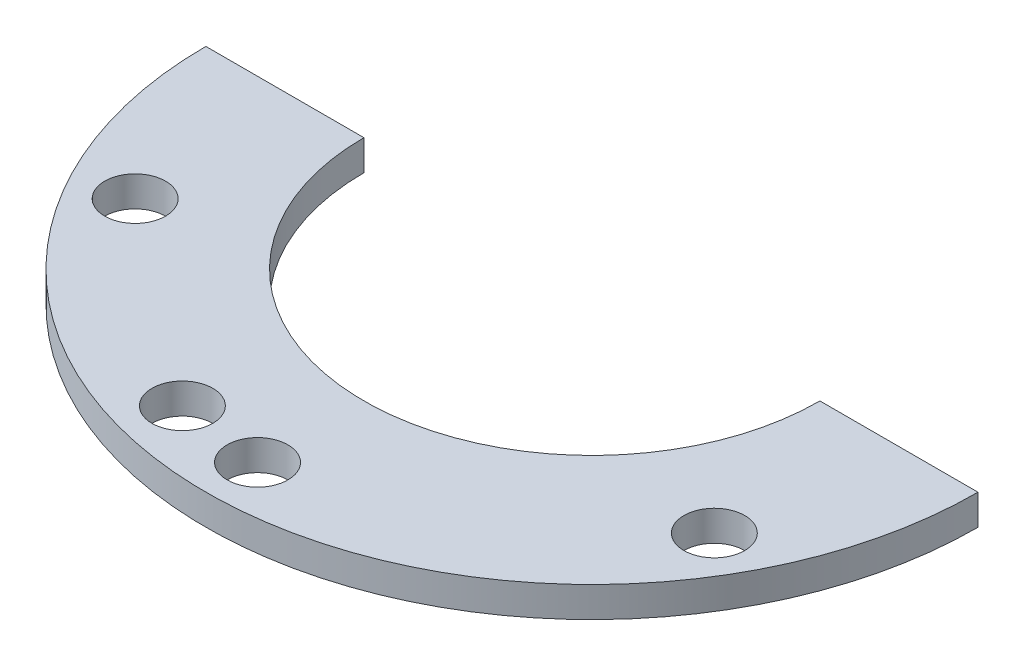
SolidWorks part; units mm, degrees
material "ABS"
ref_plane "Front Plane" through (0, 0, 0) normal (0, 0, 1) x (1, 0, 0)
ref_plane "Top Plane" through (0, 0, 0) normal (0, 1, 0) x (1, 0, 0)
ref_plane "Right Plane" through (0, 0, 0) normal (1, 0, 0) x (0, 0, -1)
sketch "Sketch1" plane through (0, 0, 0) normal (0, 1, 0) x (1, 0, 0)
  circle A0 centre (0, 0) radius 12.7
  dimension "D1" = 25.4
extrude "Boss-Extrude1" add sketch "Sketch1" along normal blind 1
sketch "Sketch19" plane through (0, 1, 0) normal (0, 1, 0) x (1, 0, 0)
  line L0 (0, 0) -> (-9.5263, -5.5) construction
  line L1 (-9.5263, -5.5) -> (0, 0) construction
  line L2 (0, 0) -> (-3.7915, -14.1501) construction
  circle A0 centre (0, 11) radius 1
  circle A1 centre (9.5263, 5.5) radius 1
  circle A2 centre (9.5263, -5.5) radius 1
  circle A3 centre (0, -11) radius 1
  circle A4 centre (-9.5263, -5.5) radius 1
  circle A5 centre (-9.5263, 5.5) radius 1
  circle A6 centre (-2.847, -10.6252) radius 1
  point P13 (0, 0)
  dimension "D1" = 2
  dimension "D4" = 2
  dimension "D2" = 11
  dimension "D5" = 11
  dimension "D6" = 0
  dimension "D3" = 6
extrude "Cut-Extrude1" cut sketch "Sketch19" against normal through all both and the other way through all
sketch "Sketch20" plane through (0, 1, 0) normal (0, 1, 0) x (1, 0, 0)
  circle A0 centre (0, 0) radius 7.5
  dimension "D1" = 15
extrude "Cut-Extrude2" cut sketch "Sketch20" against normal through all both and the other way through all
sketch "Sketch21" plane through (0, 0, 0) normal (0, 0, 1) x (1, 0, 0)
  line L1 (-36.7533, 32.3113) -> (29.1209, 32.3113)
  line L2 (-36.7533, 32.3113) -> (-36.7533, -19.668)
  line L3 (-36.7533, -19.668) -> (29.1209, -19.668)
  line L4 (29.1209, 32.3113) -> (29.1209, -19.668)
extrude "Cut-Extrude3" cut sketch "Sketch21" against normal through all
